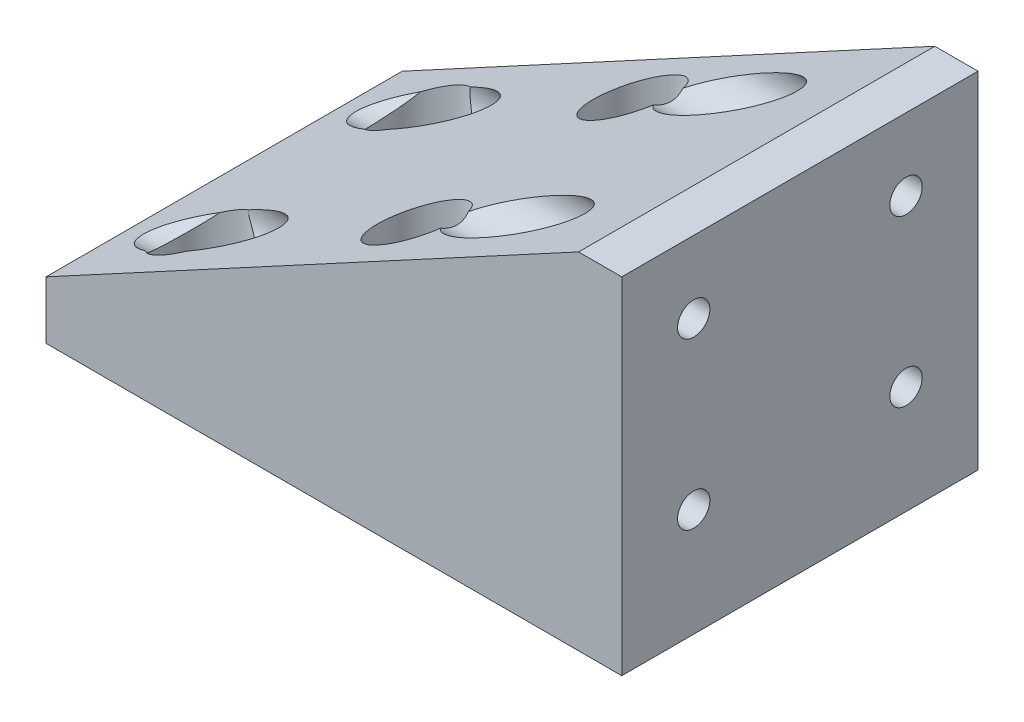
SolidWorks part; units mm, degrees
ref_plane "Front Plane" through (0, 0, 0) normal (0, 0, 1) x (1, 0, 0)
ref_plane "Top Plane" through (0, 0, 0) normal (0, 1, 0) x (1, 0, 0)
ref_plane "Right Plane" through (0, 0, 0) normal (1, 0, 0) x (0, 0, -1)
sketch "Sketch1" plane through (0, 0, 0) normal (0, 1, 0) x (1, 0, 0)
  line L1 (-40, -24.75) -> (40, -24.75)
  line L2 (-40, -24.75) -> (-40, 24.75)
  line L3 (-40, 24.75) -> (40, 24.75)
  line L4 (40, -24.75) -> (40, 24.75)
  line L5 (-40, -24.75) -> (40, 24.75) construction
  line L6 (-40, 24.75) -> (40, -24.75) construction
  point P0 (0, 0)
  point P6 (-28.25, 15)
  point P7 (-28.25, -15)
  point P8 (1.75, 15)
  point P9 (1.75, -15)
  dimension "D1" = 49.5
  dimension "D2" = 80
  dimension "D3" = 38.25
  dimension "D4" = 30
  dimension "D5" = 15
  dimension "D6" = 30
extrude "Boss-Extrude1" add sketch "Sketch1" against normal blind 8 and the other way blind 40
chamfer "Chamfer1" distance 40 distance2 74 1 edges at (-40, 40, 0)
hole_wizard "CSK for M4 SFHCS1" positions "Sketch2" profile "Sketch3" countersink size "M4" standard "ANSI Metric"
sketch "Sketch2" plane through (0, 0, 0) normal (0, 1, 0) x (1, 0, 0)
  point P0 (-28.25, 15)
  point P3 (1.75, 15)
  point P6 (1.75, -15)
  point P9 (-28.25, -15)
sketch "Sketch3" plane through (-28.25, 0, -15) normal (1, 0, 0) x (0, 0, 1)
  line L0 (0, 0) -> (0, 8)
  line L1 (0, 8) -> (2.25, 8)
  line L2 (2.25, 8) -> (2.25, 3.23)
  line L3 (2.25, 3.23) -> (5.48, 0)
  line L5 (5.48, 0) -> (0, 0)
  line L6 (-2.25, 3.23) -> (-5.48, 0) construction
  line L11 (0, -6.35) -> (0, 107.95) construction
  dimension "Thru Hole Dia." = 4.5
  dimension "Thru Hole Depth" = 8
  dimension "Near C'Sink Dia." = 10.96
  dimension "Near C'Sink Angle" = 90
sketch "Sketch4" plane through (0, 0, 0) normal (0, -1, 0) x (1, 0, 0)
  circle A0 centre (1.75, -15) radius 5.48 construction
  circle A1 centre (-28.25, -15) radius 5.48
  circle A2 centre (-28.25, -15) radius 5.48
  circle A3 centre (1.75, 15) radius 5.48 construction
  circle A4 centre (-28.25, 15) radius 5.48 construction
  circle A5 centre (1.75, -15) radius 5.48
  circle A6 centre (1.75, 15) radius 5.48
  circle A7 centre (-28.25, 15) radius 5.48
  dimension "D1" = 0
extrude "Cut-Extrude1" cut sketch "Sketch4" against normal through all
ref_plane "Plane1" through (34, 0, 0) normal (1, 0, 0) x (0, 0, -1)
ref_plane "Plane2" through (33, 0, 0) normal (1, 0, 0) x (0, 0, -1)
hole_wizard "CSK for #8 Flat Head Machine Screw1" positions "Sketch5" profile "Sketch6" countersink size "#8" standard "ANSI Inch"
sketch "Sketch5" plane through (33, 0, 0) normal (1, 0, 0) x (0, 0, -1)
  line L0 (-24.75, 40) -> (24.75, 40) construction
  line L1 (-24.75, 40) -> (-24.75, -8) construction
  line L2 (-24.75, -8) -> (24.75, -8) construction
  line L3 (24.75, 40) -> (24.75, -8) construction
  point P0 (-14.75, 30)
  point P2 (14.75, 30)
  point P4 (14.75, 7)
  point P6 (-14.75, 7)
  dimension "D1" = 10
  dimension "D2" = 10
  dimension "D3" = 15
  dimension "D4" = 10
sketch "Sketch6" plane through (33, 30, 14.75) normal (0, 1, 0) x (0, 0, 1)
  line L0 (0, 0) -> (0, 7)
  line L1 (0, 7) -> (2.2479, 7)
  line L2 (2.2479, 7) -> (2.2479, 3.2645)
  line L3 (2.2479, 3.2645) -> (5.0857, 0)
  line L5 (5.0857, 0) -> (0, 0)
  line L6 (-2.2479, 3.2645) -> (-5.0857, 0) construction
  line L11 (0, -6.35) -> (0, 107.95) construction
  dimension "Thru Hole Dia." = 4.4958
  dimension "Thru Hole Depth" = 7
  dimension "Near C'Sink Dia." = 10.1714
  dimension "Near C'Sink Angle" = 82
sketch "Sketch7" plane through (33, 0, 0) normal (1, 0, 0) x (0, 0, -1)
  circle A0 centre (-14.75, 7) radius 5.0857 construction
  circle A1 centre (14.75, 7) radius 5.0857 construction
  circle A2 centre (14.75, 30) radius 5.0857 construction
  circle A3 centre (-14.75, 30) radius 5.0857 construction
  circle A4 centre (-14.75, 7) radius 5.0857
  circle A5 centre (14.75, 7) radius 5.0857
  circle A6 centre (14.75, 30) radius 5.0857
  circle A7 centre (-14.75, 30) radius 5.0857
extrude "Cut-Extrude2" cut sketch "Sketch7" against normal through all
